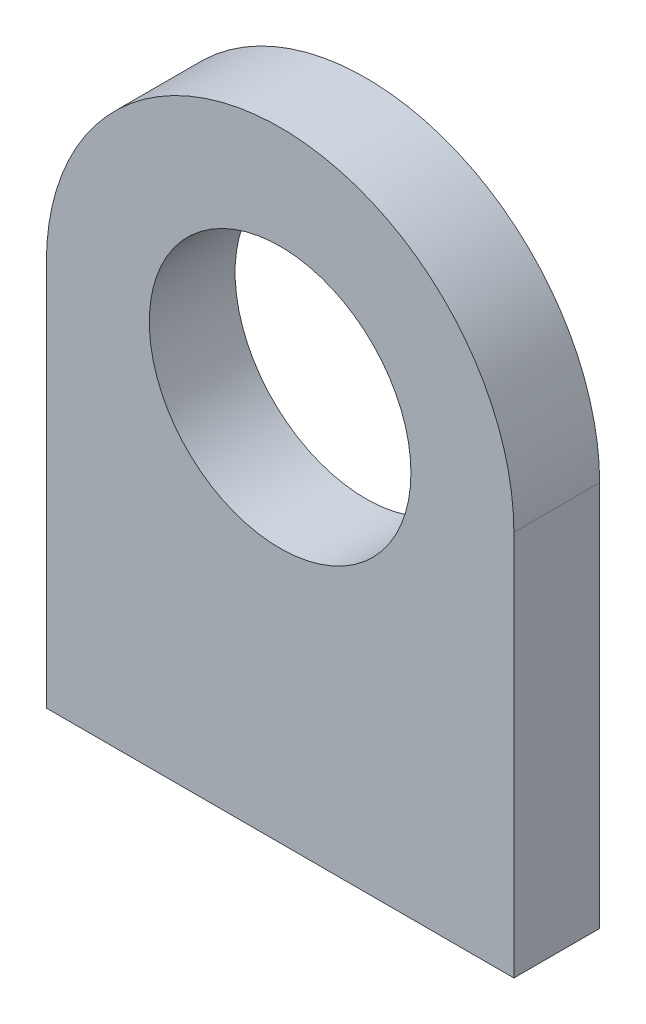
SolidWorks part; units mm, degrees
material "1023 탄소 강판(SS)"
ref_plane "정면" through (0, 0, 0) normal (0, 0, 1) x (1, 0, 0)
ref_plane "윗면" through (0, 0, 0) normal (0, 1, 0) x (1, 0, 0)
ref_plane "우측면" through (0, 0, 0) normal (1, 0, 0) x (0, 0, -1)
sketch "스케치1" plane through (0, 0, 0) normal (0, 0, 1) x (1, 0, 0)
  line L0 (0, 38.869) -> (0, -49.2447) construction
  line L1 (-10.9, 20.334) -> (-10.9, 2.334)
  line L2 (10.9, 20.334) -> (10.9, 2.334)
  line L3 (-10.9, 2.334) -> (-8.65, 2.334)
  line L4 (8.65, 2.334) -> (10.9, 2.334)
  line L5 (-8.65, 2.334) -> (8.65, 2.334)
  circle A0 centre (0, 20.334) radius 6.1
  arc A1 (10.9, 20.334) -> (-10.9, 20.334) centre (0, 20.334) ccw
  point P5 (10.9, 26.234)
  dimension "D1" = 12.2
  dimension "D2" = 21.8
  dimension "D3" = 18
  dimension "D4" = 2.25
  dimension "D5" = 2.25
extrude "보스-돌출1" add sketch "스케치1" along normal blind 4
